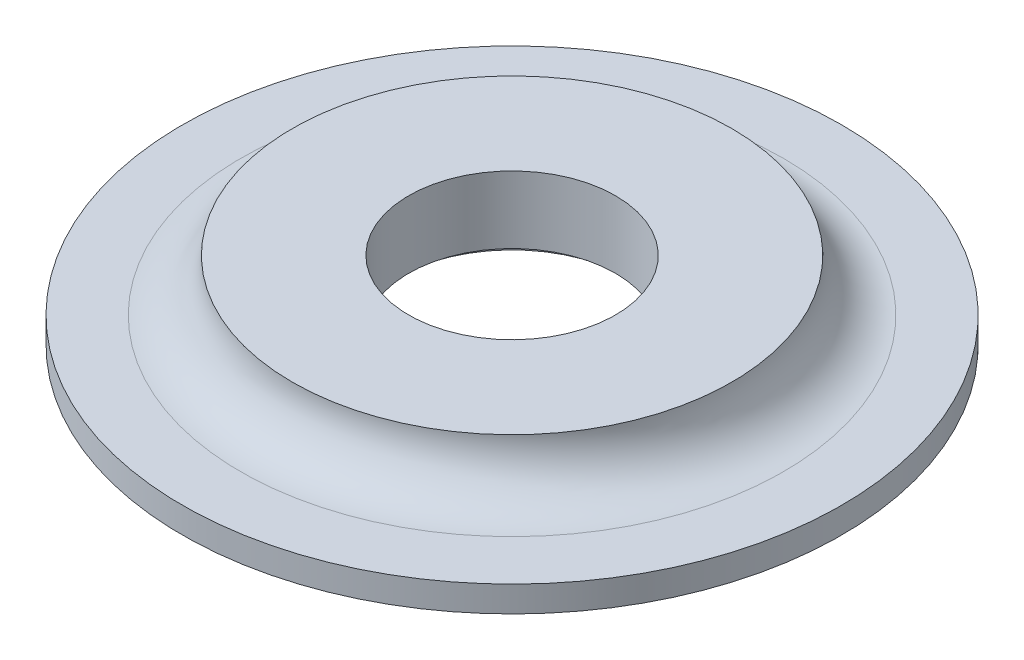
SolidWorks part; units mm, degrees
ref_plane "Спереди" through (0, 0, 0) normal (0, 0, 1) x (1, 0, 0)
ref_plane "Сверху" through (0, 0, 0) normal (0, 1, 0) x (1, 0, 0)
ref_plane "Справа" through (0, 0, 0) normal (1, 0, 0) x (0, 0, -1)
sketch "Эскиз1" plane through (0, 0, 0) normal (0, 0, 1) x (1, 0, 0)
  line L0 (9, 0) -> (25.5, 0)
  line L1 (-29.9808, 6) -> (45.5679, 6) construction
  line L2 (21, 21.5267) -> (21, -18.394) construction
  line L3 (21, 2) -> (25.5, 2)
  line L4 (25.5, 2) -> (25.5, 0)
  line L5 (17, 6) -> (8, 6)
  line L6 (0, 0) -> (0, 16.6582) construction
  line L7 (8, 6) -> (8, 0.8)
  line L8 (8, 0.8) -> (9, 0.8)
  line L9 (9, 0.8) -> (9, 0)
  arc A0 (17, 6) -> (21, 2) centre (21, 6) ccw
  dimension "D3" = 8
  dimension "D6" = 9
  dimension "D1" = 25.5
  dimension "D2" = 6
  dimension "D4" = 21
  dimension "D5" = 8
  dimension "D7" = 0.8
revolve "Повернуть1" add sketch "Эскиз1" angle 360 about L6
